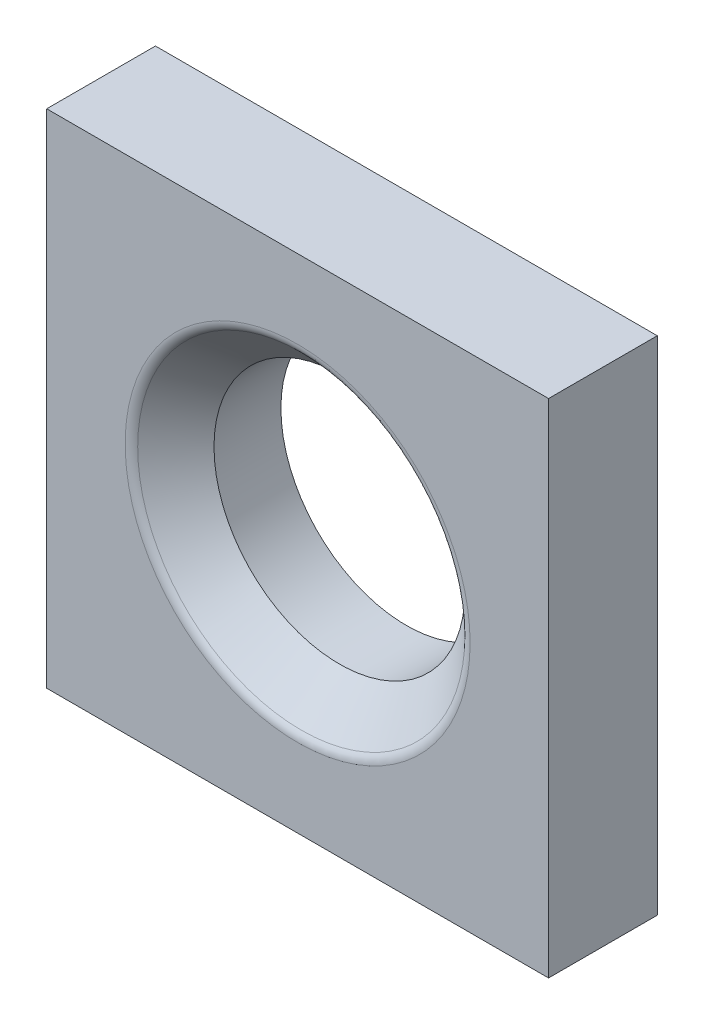
SolidWorks part; units mm, degrees
ref_plane "Front Plane" through (0, 0, 0) normal (0, 0, 1) x (1, 0, 0)
ref_plane "Top Plane" through (0, 0, 0) normal (0, 1, 0) x (1, 0, 0)
ref_plane "Right Plane" through (0, 0, 0) normal (1, 0, 0) x (0, 0, -1)
sketch "Sketch1" plane through (0, 0, 0) normal (0, 0, 1) x (1, 0, 0)
  line L1 (30, -30) -> (-30, -30)
  line L2 (30, -30) -> (30, 30)
  line L3 (30, 30) -> (-30, 30)
  line L4 (-30, -30) -> (-30, 30)
  line L5 (30, -30) -> (-30, 30) construction
  line L6 (30, 30) -> (-30, -30) construction
  circle A0 centre (0, 0) radius 15
  point P0 (0, 0)
  dimension "D1" = 30
  dimension "D2" = 60
extrude "Boss-Extrude1" add sketch "Sketch1" along normal blind 13
chamfer "Chamfer1" distance 5 angle 45 1 edges at (15, 0, 13)
fillet "Fillet1" radius 1.5 1 edges at (20, 0, 13)
